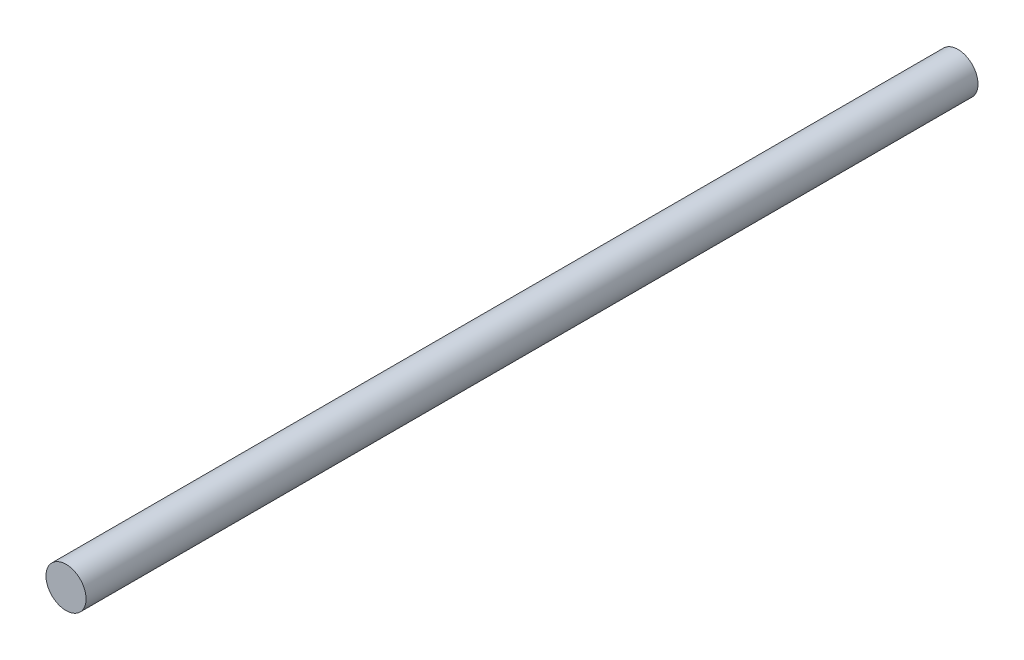
SolidWorks part; units mm, degrees
ref_plane "Piano frontale" through (0, 0, 0) normal (0, 0, 1) x (1, 0, 0)
ref_plane "Piano superiore" through (0, 0, 0) normal (0, 1, 0) x (1, 0, 0)
ref_plane "Piano destro" through (0, 0, 0) normal (1, 0, 0) x (0, 0, -1)
sketch "Schizzo1" plane through (0, 0, 0) normal (0, 0, 1) x (1, 0, 0)
  line L0 (0, 0) -> (0, 38.2658) construction
  circle A13 centre (0, 0) radius 9
  point P46 (0, 0)
  dimension "D1" = 18
extrude "Estrusione-Estrusione1" add sketch "Schizzo1" along normal blind 400
